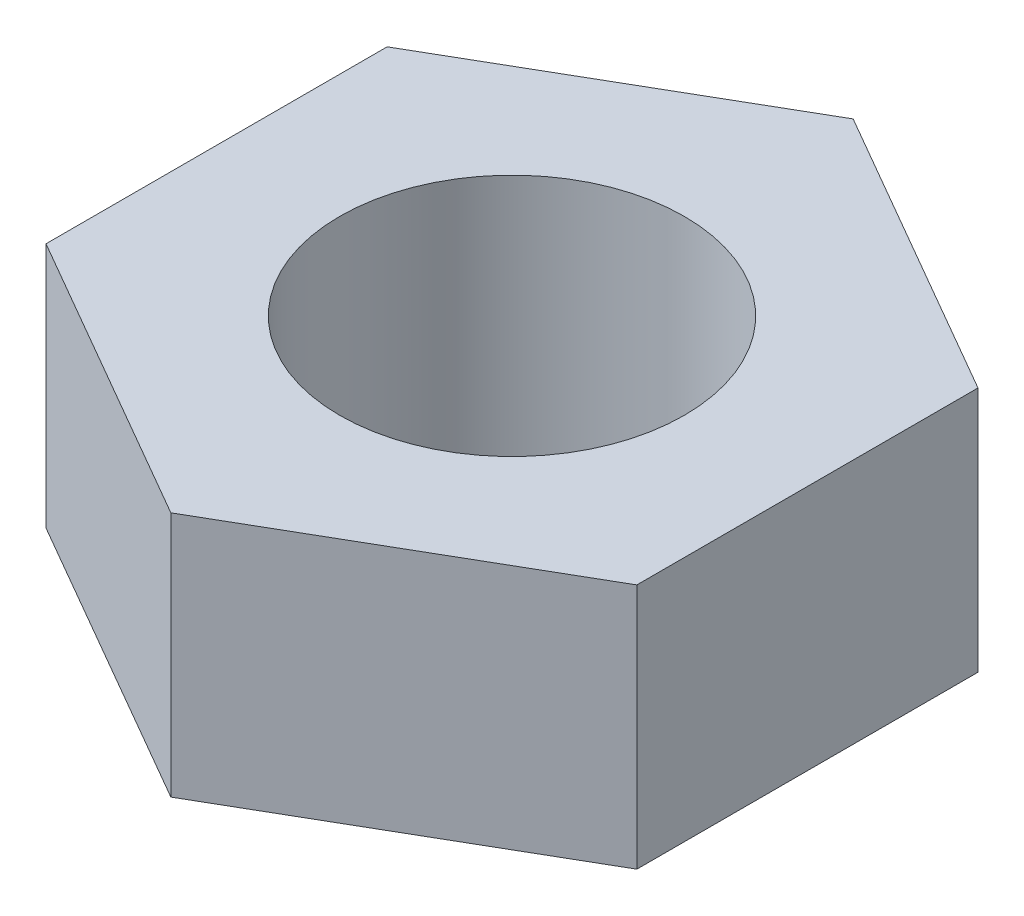
SolidWorks part; units mm, degrees
ref_plane "Front Plane" through (0, 0, 0) normal (0, 0, 1) x (1, 0, 0)
ref_plane "Top Plane" through (0, 0, 0) normal (0, 1, 0) x (1, 0, 0)
ref_plane "Right Plane" through (0, 0, 0) normal (1, 0, 0) x (0, 0, -1)
sketch "Sketch1" plane through (0, 0, 0) normal (0, 1, 0) x (1, 0, 0)
  line L1 (-12, -6.9282) -> (0, -13.8564)
  line L2 (0, -13.8564) -> (12, -6.9282)
  line L3 (12, -6.9282) -> (12, 6.9282)
  line L4 (12, 6.9282) -> (0, 13.8564)
  line L5 (0, 13.8564) -> (-12, 6.9282)
  line L6 (-12, 6.9282) -> (-12, -6.9282)
  circle A0 centre (0, 0) radius 12 construction
  circle A1 centre (0, 0) radius 7
  dimension "D2" = 14
  dimension "D1" = 24
extrude "Boss-Extrude1" add sketch "Sketch1" along normal blind 10
